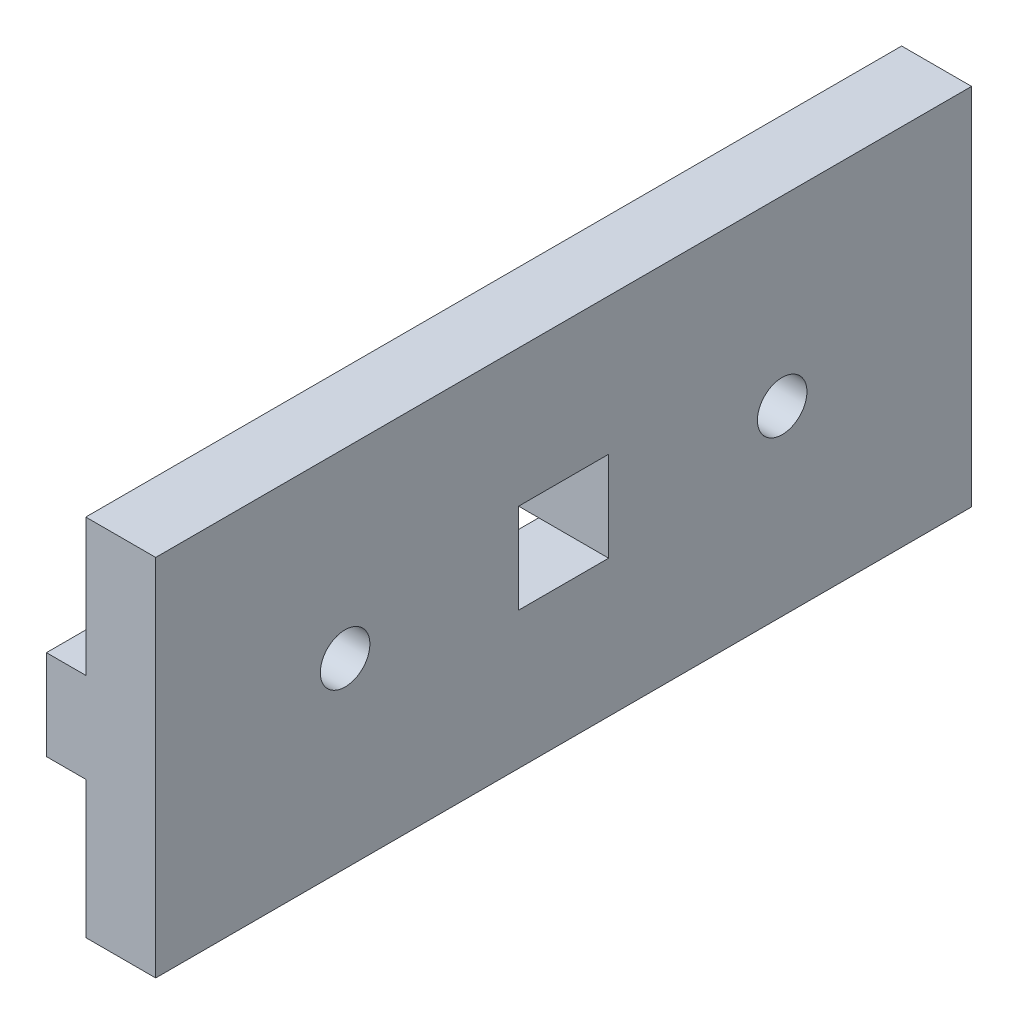
SolidWorks part; units mm, degrees
ref_plane "Front Plane" through (0, 0, 0) normal (0, 0, 1) x (1, 0, 0)
ref_plane "Top Plane" through (0, 0, 0) normal (0, 1, 0) x (1, 0, 0)
ref_plane "Right Plane" through (0, 0, 0) normal (1, 0, 0) x (0, 0, -1)
sketch "Sketch1" plane through (0, 0, 0) normal (0, 0, 1) x (1, 0, 0)
  line L0 (9.1279, 7.8486) -> (9.1279, 0)
  line L1 (9.1279, 0) -> (12.5569, 0)
  line L2 (12.5569, 0) -> (12.5569, -11.9507)
  line L3 (12.5569, -11.9507) -> (18.6529, -11.9507)
  line L4 (18.6529, -11.9507) -> (18.6529, 19.7993)
  line L5 (18.6529, 19.7993) -> (12.5569, 19.7993)
  line L6 (12.5569, 19.7993) -> (12.5569, 7.8486)
  line L7 (12.5569, 7.8486) -> (9.1279, 7.8486)
  dimension "D1" = 7.8486
  dimension "D2" = 31.75
  dimension "D3" = 6.096
  dimension "D4" = 9.525
extrude "Boss-Extrude1" add sketch "Sketch1" along normal blind 71.12
sketch "Sketch2" plane through (9.1279, 0, 0) normal (-1, 0, 0) x (0, 0, 1)
  line L0 (0, 3.9243) -> (71.12, 3.9243) construction
  line L1 (0, 7.8486) -> (0, 0) construction
  line L2 (71.12, 7.8486) -> (71.12, 0) construction
  circle A0 centre (16.51, 3.9243) radius 6
  circle A1 centre (54.61, 3.9243) radius 6
  dimension "D2" = 12
  dimension "D3" = 16.51
  dimension "D4" = 16.51
extrude "Cut-Extrude1" cut sketch "Sketch2" against normal blind 4 contours A0 | A1
sketch "Sketch3" plane through (13.1279, 0, 0) normal (-1, 0, 0) x (0, 0, 1)
  circle A0 centre (16.51, 3.9243) radius 2.16
  circle A1 centre (54.61, 3.9243) radius 2.16
  dimension "D1" = 4.32
extrude "Cut-Extrude2" cut sketch "Sketch3" against normal up to next contours A0 | A1
sketch "Sketch5" plane through (9.1279, 0, 0) normal (-1, 0, 0) x (0, 0, 1)
  line L0 (0, 3.9243) -> (71.12, 3.9243) construction
  line L1 (0, 7.8486) -> (0, 0) construction
  line L2 (71.12, 7.8486) -> (71.12, 0) construction
  line L3 (50.0713, 7.8486) -> (21.0487, 7.8486) construction
  line L4 (31.6357, 0) -> (39.4843, 0)
  line L5 (31.6357, 0) -> (31.6357, 7.8486)
  line L6 (31.6357, 7.8486) -> (39.4843, 7.8486)
  line L7 (39.4843, 0) -> (39.4843, 7.8486)
  line L8 (31.6357, 0) -> (39.4843, 7.8486) construction
  line L9 (31.6357, 7.8486) -> (39.4843, 0) construction
  point P6 (35.56, 3.9243)
extrude "Cut-Extrude3" cut sketch "Sketch5" against normal up to next contours L5 L4 L7 L6
